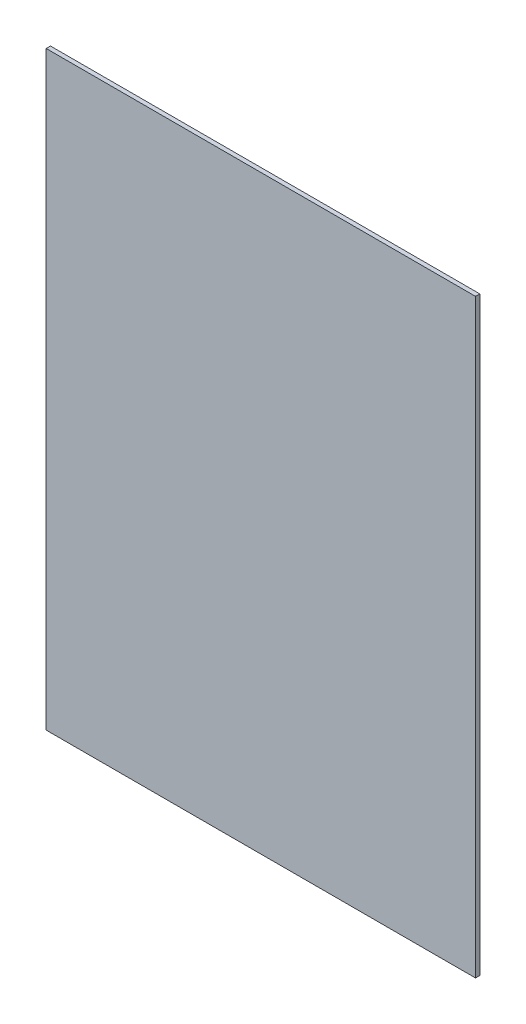
SolidWorks part; units mm, degrees
ref_plane "Plan de face" through (0, 0, 0) normal (0, 0, 1) x (1, 0, 0)
ref_plane "Plan de dessus" through (0, 0, 0) normal (0, 1, 0) x (1, 0, 0)
ref_plane "Plan de droite" through (0, 0, 0) normal (1, 0, 0) x (0, 0, -1)
sketch "Esquisse1" plane through (0, 0, 0) normal (0, 0, 1) x (1, 0, 0)
  line L1 (-200, 275) -> (200, 275)
  line L2 (-200, 275) -> (-200, -275)
  line L3 (-200, -275) -> (200, -275)
  line L4 (200, 275) -> (200, -275)
  line L5 (-200, 275) -> (200, -275) construction
  line L6 (-200, -275) -> (200, 275) construction
  point P0 (0, 0)
  dimension "D1" = 400
  dimension "D2" = 550
extrude "Boss.-Extru.1" add sketch "Esquisse1" along normal blind 4
